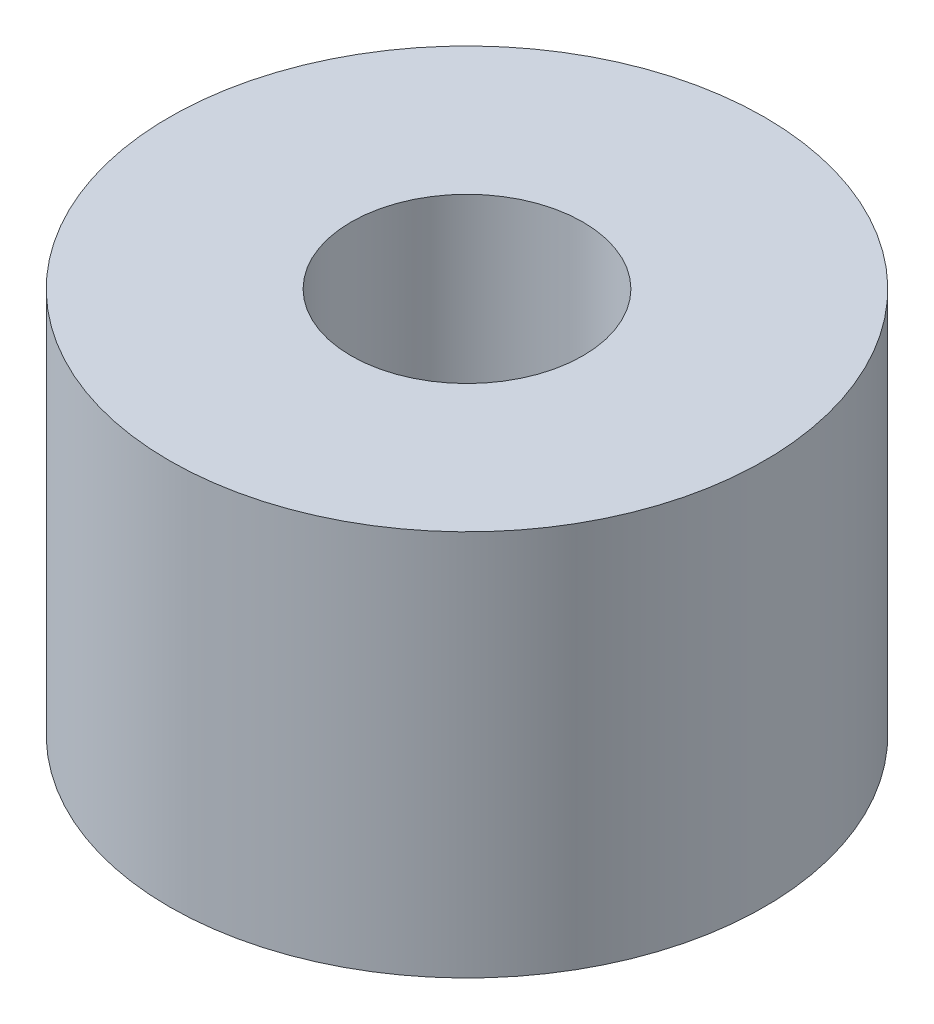
SolidWorks part; units mm, degrees
ref_plane "Front Plane" through (0, 0, 0) normal (0, 0, 1) x (1, 0, 0)
ref_plane "Top Plane" through (0, 0, 0) normal (0, 1, 0) x (1, 0, 0)
ref_plane "Right Plane" through (0, 0, 0) normal (1, 0, 0) x (0, 0, -1)
sketch "Sketch1" plane through (0, 0, 0) normal (0, 1, 0) x (1, 0, 0)
  circle A0 centre (0, 0) radius 7.7
extrude "Boss-Extrude1" add sketch "Sketch1" along normal blind 10
sketch "Sketch2" plane through (0, 10, 0) normal (0, 1, 0) x (1, 0, 0)
  circle A0 centre (0, 0) radius 3
extrude "Cut-Extrude1" cut sketch "Sketch2" against normal blind 5
